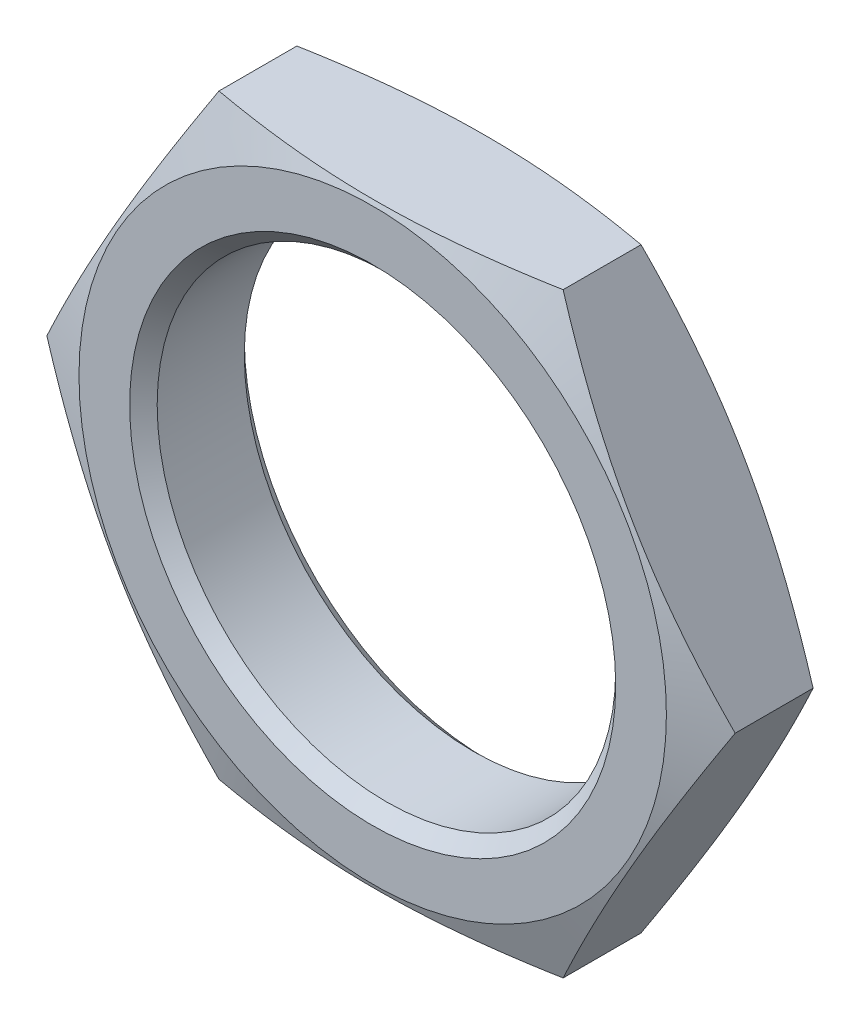
SolidWorks part; units mm, degrees
material "Acier non allié"
ref_plane "Plan de face" through (0, 0, 0) normal (0, 0, 1) x (1, 0, 0)
ref_plane "Plan de dessus" through (0, 0, 0) normal (0, 1, 0) x (1, 0, 0)
ref_plane "Plan de droite" through (0, 0, 0) normal (1, 0, 0) x (0, 0, -1)
sketch "Esquisse1" plane through (0, 0, 0) normal (0, 0, 1) x (1, 0, 0)
  line L1 (7.5056, 0) -> (3.7528, 6.5)
  line L2 (3.7528, 6.5) -> (-3.7528, 6.5)
  line L3 (-3.7528, 6.5) -> (-7.5056, 0)
  line L4 (-7.5056, 0) -> (-3.7528, -6.5)
  line L5 (-3.7528, -6.5) -> (3.7528, -6.5)
  line L6 (3.7528, -6.5) -> (7.5056, 0)
  circle A0 centre (0, 0) radius 6.5 construction
  circle A1 centre (0, 0) radius 5
  dimension "D2" = 10
  dimension "D1" = 13
extrude "Boss.-Extru.1" add sketch "Esquisse1" along normal blind 2.5
sketch "Esquisse2" plane through (0, 0, 0) normal (0, 1, 0) x (1, 0, 0)
  line L0 (-6.4056, 0) -> (-7.5056, -0.4004)
  line L1 (-7.5056, -0.4004) -> (-7.5056, -2.0996)
  line L2 (-7.5056, -2.0996) -> (-6.4056, -2.5)
  line L3 (-6.4056, -2.5) -> (-9.0056, -2.5)
  line L4 (-9.0056, -2.5) -> (-9.0056, 0)
  line L5 (-9.0056, 0) -> (-6.4056, 0)
  line L6 (-7.5056, -2.5) -> (-7.5056, 0) construction
  line L8 (-3.7528, 0) -> (-7.5056, 0) construction
  line L9 (-3.7528, -2.5) -> (-7.5056, -2.5) construction
  line L10 (-6.4056, 0) -> (-6.4056, -2.5) construction
  line L11 (0, 0) -> (0, -2.5) construction
  line L12 (3.7528, -2.5) -> (-3.7528, -2.5) construction
  dimension "D1" = 20
  dimension "D2" = 20
  dimension "D3" = 1.5
  dimension "D4" = 1.1
revolve "Enlèvement de matière-Révolution1" cut sketch "Esquisse2" angle 360 about L11
chamfer "Chanfrein1" distance 0.3 angle 45 2 edges at (5, 0, 2.5) (5, 0, 0)
